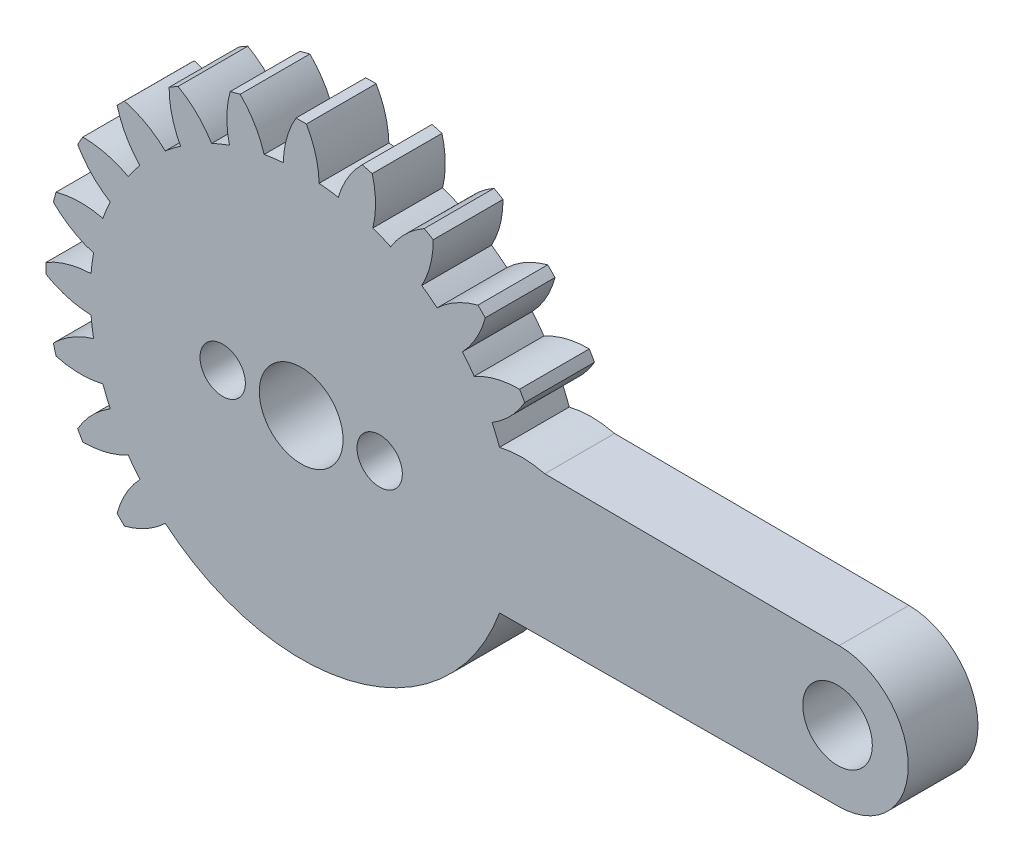
SolidWorks part; units mm, degrees
material "Acrylic (Medium-high impact)"
ref_plane "Front Plane" through (0, 0, 0) normal (0, 0, 1) x (1, 0, 0)
ref_plane "Top Plane" through (0, 0, 0) normal (0, 1, 0) x (1, 0, 0)
ref_plane "Right Plane" through (0, 0, 0) normal (1, 0, 0) x (0, 0, -1)
sketch "Sketch1" plane through (0, 0, 0) normal (0, 0, 1) x (1, 0, 0)
  line L0 (0, 0) -> (0, 8.7244) construction
  line L1 (0, 12.09) -> (0, 14.63) construction
  line L2 (0, 0) -> (30.75, 0) construction
  line L3 (11.3698, -4.1104) -> (30.8258, -3.9999)
  line L4 (30.8419, 3.9998) -> (11.3698, 4.1104)
  circle A0 centre (0, 0) radius 1.75
  circle A1 centre (0, 0) radius 12.09
  circle A2 centre (0, 0) radius 14.63
  arc A3 (0.297, 14.627) -> (1.0278, 12.0462) centre (-4.3706, 11.9115) cw
  arc A4 (-0.297, 14.627) -> (-1.0278, 12.0462) centre (4.3706, 11.9115) ccw
  arc A5 (3.4989, 14.2054) -> (2.1252, 11.9017) centre (7.3048, 10.3746) ccw
  arc A6 (4.0729, 14.0516) -> (4.1107, 11.3697) centre (-1.1385, 12.637) cw
  arc A7 (7.0563, 12.8158) -> (5.1333, 10.9461) centre (9.7413, 8.1307) ccw
  arc A8 (7.5712, 12.5185) -> (6.9135, 9.9183) centre (2.1713, 12.5012) cw
  arc A9 (10.1327, 10.5529) -> (7.7915, 9.2445) centre (11.514, 5.3326) ccw
  arc A10 (10.5534, 10.1322) -> (9.245, 7.791) centre (5.3331, 11.5135) cw
  arc A11 (12.5187, 7.571) -> (9.9186, 6.9129) centre (12.5021, 2.171) ccw
  arc A12 (12.8163, 7.0554) -> (10.9464, 5.1327) centre (8.1315, 9.7411) cw
  arc A13 (13.9662, 4.0956) -> (11.3698, 4.1104) centre (12.6382, -1.1386) ccw
  arc A14 (14.2057, 3.4978) -> (11.9018, 2.1248) centre (10.3759, 7.3047) cw
  arc A15 (14.627, 0.298) -> (12.0462, 1.0278) centre (11.9132, -4.3706) ccw
  arc A16 (14.627, -0.298) -> (12.0462, -1.0278) centre (11.9132, 4.3705) cw
  arc A17 (14.2058, -3.4976) -> (11.9018, -2.1248) centre (10.3763, -7.3048) ccw
  arc A18 (14.0515, -4.0735) -> (11.3698, -4.1104) centre (12.6387, 1.1384) cw
  arc A19 (12.8166, -7.0548) -> (10.9465, -5.1326) centre (8.1324, -9.7413) ccw
  arc A20 (12.5185, -7.5713) -> (9.9187, -6.9128) centre (12.5029, -2.1713) cw
  arc A21 (10.5542, -10.1314) -> (9.2453, -7.7906) centre (5.3343, -11.514) ccw
  arc A22 (10.1326, -10.5531) -> (7.7918, -9.2442) centre (11.5152, -5.3331) cw
  arc A23 (7.5727, -12.5176) -> (6.9141, -9.9178) centre (2.1727, -12.5021) ccw
  arc A24 (7.0562, -12.8159) -> (5.134, -10.9458) centre (9.7427, -8.1315) cw
  arc A25 (4.0751, -14.051) -> (4.1119, -11.3693) centre (-1.1369, -12.6383) ccw
  arc A26 (3.4992, -14.2054) -> (2.1264, -11.9015) centre (7.3064, -10.3759) cw
  arc A27 (0.2997, -14.6269) -> (1.0295, -12.0461) centre (-4.3689, -11.9132) ccw
  arc A28 (-0.2963, -14.627) -> (-1.0261, -12.0464) centre (4.3722, -11.9132) cw
  arc A29 (-3.4962, -14.2061) -> (-2.1232, -11.9021) centre (-7.3032, -10.3763) ccw
  arc A30 (-4.0716, -14.052) -> (-4.1088, -11.3704) centre (1.1401, -12.6387) cw
  arc A31 (-7.0539, -12.8171) -> (-5.1312, -10.9471) centre (-9.7397, -8.1324) ccw
  arc A32 (-7.5696, -12.5195) -> (-6.9116, -9.9196) centre (-2.1696, -12.5029) cw
  arc A33 (-10.131, -10.5546) -> (-7.7897, -9.246) centre (-11.5123, -5.3343) ccw
  arc A34 (-10.5518, -10.1339) -> (-9.2434, -7.7928) centre (-5.3314, -11.5152) cw
  arc A35 (-12.5176, -7.5727) -> (-9.9173, -6.9148) centre (-12.5004, -2.1727) ccw
  arc A36 (-12.815, -7.0577) -> (-10.9454, -5.1348) centre (-8.1299, -9.7428) cw
  arc A37 (-14.0511, -4.0746) -> (-11.3691, -4.1123) centre (-12.6366, 1.1368) ccw
  arc A38 (-14.205, -3.5005) -> (-11.9014, -2.1269) centre (-10.3742, -7.3064) cw
  arc A39 (-14.627, -0.2987) -> (-12.0461, -1.0294) centre (-11.9115, 4.3689) ccw
  arc A40 (-14.627, 0.2953) -> (-12.0464, 1.0261) centre (-11.9115, -4.3722) cw
  arc A41 (-14.2058, 3.4976) -> (-11.902, 2.1236) centre (-10.3746, 7.3031) ccw
  arc A42 (-14.0521, 4.0711) -> (-11.3703, 4.1092) centre (-12.637, -1.1401) cw
  arc A43 (-12.8163, 7.0554) -> (-10.9467, 5.132) centre (-8.1307, 9.7396) ccw
  arc A44 (-12.5195, 7.5696) -> (-9.9191, 6.9122) centre (-12.5013, 2.1696) cw
  arc A45 (-10.5533, 10.1324) -> (-9.2452, 7.7906) centre (-5.3326, 11.5123) ccw
  arc A46 (-10.1336, 10.5521) -> (-7.7919, 9.2442) centre (-11.5135, 5.3314) cw
  arc A47 (-7.571, 12.5187) -> (-6.9136, 9.9182) centre (-2.171, 12.5004) ccw
  arc A48 (-7.0569, 12.8155) -> (-5.1336, 10.946) centre (-9.7411, 8.1298) cw
  arc A49 (-4.0728, 14.0517) -> (-4.1108, 11.3697) centre (1.1385, 12.6366) ccw
  arc A50 (-3.4992, 14.2054) -> (-2.1253, 11.9017) centre (-7.3048, 10.3742) cw
  circle A51 centre (30.75, 0) radius 1.995
  arc A52 (30.8258, -3.9999) -> (30.8419, 3.9998) centre (30.8031, 0) ccw
  point P105 (0.0008, -0.0009)
  dimension "D1" = 3.5
  dimension "D2" = 24.18
  dimension "D3" = 29.26
  dimension "D4" = 5.4
  dimension "D7" = 3.99
  dimension "D8" = 4
  dimension "D5" = 24
  dimension "D6" = 30.75
extrude "Boss-Extrude1" add sketch "Sketch1" along normal blind 4 contours A1 A0 | L3 A52 L4 A2 A51 | A14 A2 L4 A1 | A36 A2 A35 A1 | A38 A2 A37 A1 | A40 A2 A39 A1 | A42 A2 A41 A1 | A44 A2 A43 A1 | A46 A2 A45 A1 | A48 A2 A47 A1 | A50 A2 A49 A1 | A2 A4 A1 A3 | A6 A2 A5 A1 | A8 A2 A7 A1 | A10 A2 A9 A1 | A12 A2 A11 A1 | A17 A2 A16 A1 | A18 A2 A17 A1 L3 | A16 A2 A15 A1 | A15 A2 A14 A1 | L4 A13 | A34 A2 A33 A1
sketch "Sketch2" plane through (0, 0, 4) normal (0, 0, 1) x (1, 0, 0)
  line L0 (-4.5, 0) -> (4.5, 0) construction
  circle A0 centre (4.5, 0) radius 1.3
  circle A1 centre (-4.5, 0) radius 1.3
  circle A2 centre (0, 0) radius 2.4
  point P7 (0, 0)
  dimension "D1" = 4.8
  dimension "D2" = 2.6
  dimension "D3" = 9
extrude "Cut-Extrude1" cut sketch "Sketch2" against normal through all
